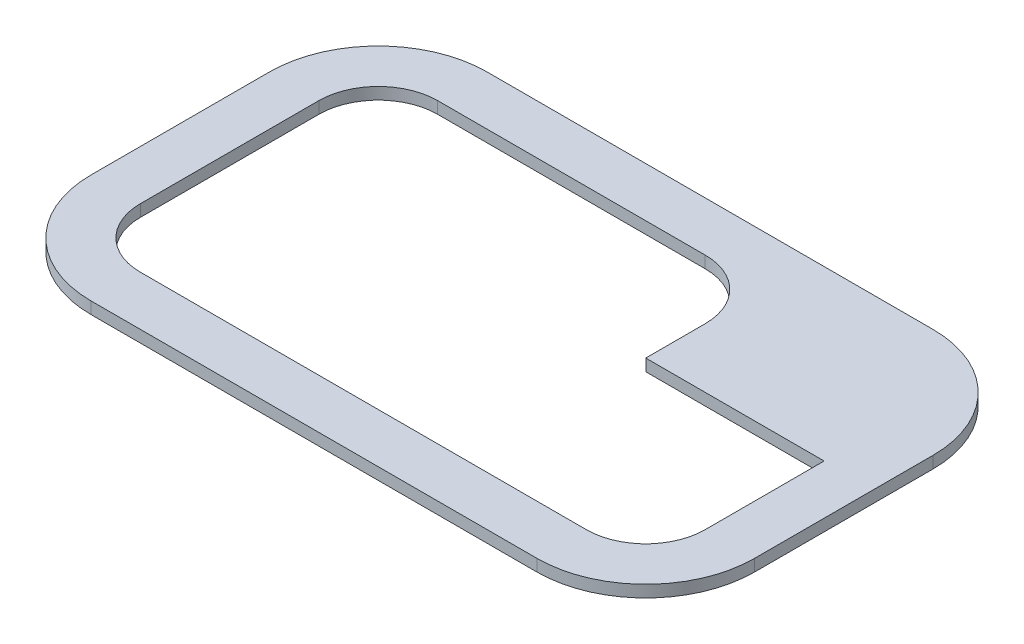
SolidWorks part; units mm, degrees
ref_plane "Front Plane" through (0, 0, 0) normal (0, 0, 1) x (1, 0, 0)
ref_plane "Top Plane" through (0, 0, 0) normal (0, 1, 0) x (1, 0, 0)
ref_plane "Right Plane" through (0, 0, 0) normal (1, 0, 0) x (0, 0, -1)
sketch "Sketch1" plane through (0, 0, 0) normal (0, 1, 0) x (1, 0, 0)
  line L0 (0, -30) -> (225, -30)
  line L1 (0, -55) -> (225, -55)
  line L2 (-55, 0) -> (-55, 90)
  line L3 (0, 145) -> (225, 145)
  line L4 (280, 0) -> (280, 90)
  line L5 (0, 120) -> (135, 120)
  line L6 (165, 90) -> (165, 60)
  line L7 (-30, 0) -> (-30, 90)
  line L8 (165, 60) -> (255, 60)
  line L9 (255, 60) -> (255, 0)
  line L12 (0, 120) -> (225, 120) construction
  line L13 (255, 0) -> (255, 90) construction
  arc A0 (225, 145) -> (280, 90) centre (225, 90) cw
  arc A1 (225, -55) -> (280, 0) centre (225, 0) ccw
  arc A2 (0, -55) -> (-55, 0) centre (0, 0) cw
  arc A3 (-55, 90) -> (0, 145) centre (0, 90) cw
  arc A4 (225, -30) -> (255, 0) centre (225, 0) ccw
  arc A5 (135, 120) -> (165, 90) centre (135, 90) cw
  arc A6 (-30, 90) -> (0, 120) centre (0, 90) cw
  arc A7 (0, -30) -> (-30, 0) centre (0, 0) cw
  arc A12 (225, 120) -> (255, 90) centre (225, 90) cw construction
  point P6 (280, 145)
  point P11 (-55, -55)
  point P14 (-55, 145)
  dimension "D3" = 55
  dimension "D5" = 30
  dimension "D1" = 335
  dimension "D2" = 200
  dimension "D6" = 135
  dimension "D7" = 60
  dimension "D4" = 25
extrude "Boss-Extrude1" add sketch "Sketch1" along normal blind 6
